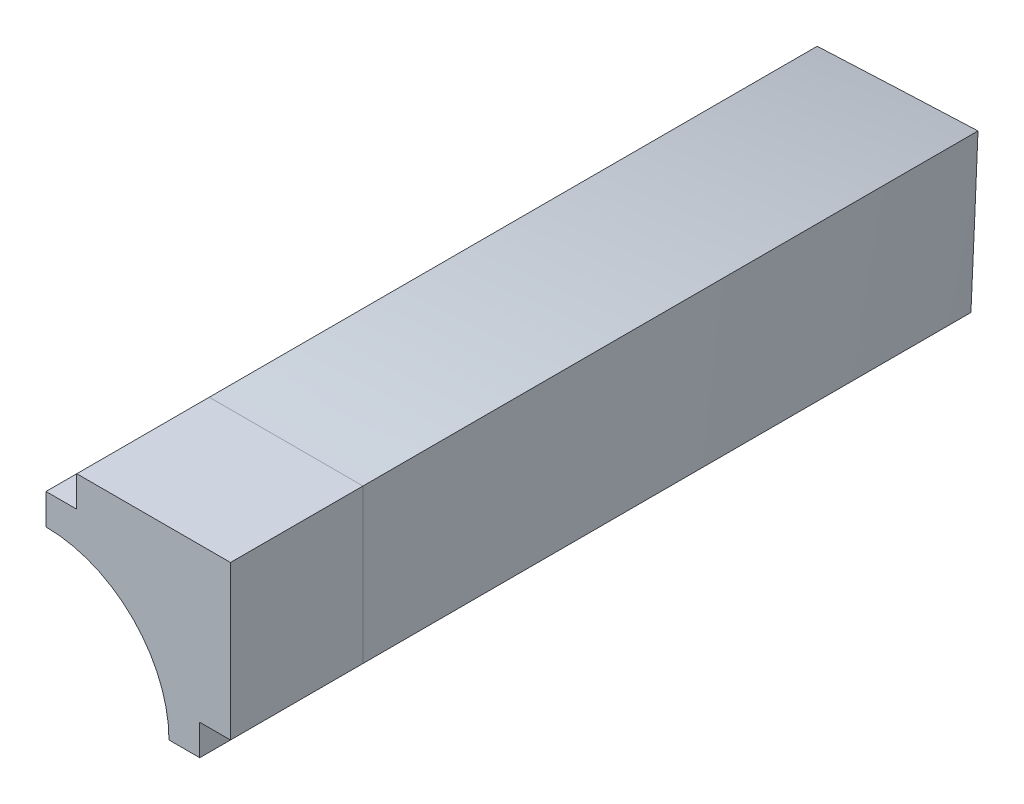
SolidWorks part; units mm, degrees
material "PET"
ref_plane "Front Plane" through (0, 0, 0) normal (0, 0, 1) x (1, 0, 0)
ref_plane "Top Plane" through (0, 0, 0) normal (0, 1, 0) x (1, 0, 0)
ref_plane "Right Plane" through (0, 0, 0) normal (1, 0, 0) x (0, 0, -1)
sketch "Sketch1" plane through (0, 0, 0) normal (0, 0, 1) x (1, 0, 0)
  line L0 (325, 305) -> (330, 305)
  line L1 (330, 305) -> (330, 310)
  line L2 (330, 310) -> (335, 310)
  line L3 (335, -335) -> (335, 335) construction
  line L4 (335, 310) -> (335, 335)
  line L5 (335, 335) -> (310, 335)
  line L6 (335, 335) -> (-335, 335) construction
  line L7 (310, 335) -> (310, 330)
  line L8 (310, 330) -> (305, 330)
  line L9 (305, 330) -> (305, 325)
  arc A0 (325, 305) -> (305, 325) centre (305, 305) ccw construction
  arc A1 (325, 305) -> (305, 325) centre (305, 305) ccw
  dimension "D1" = 5
  dimension "D2" = 5
extrude "Boss-Extrude1" add sketch "Sketch1" against normal up to vertex (21.5428 mm away)
sketch "Sketch3" plane through (0, 0, -21.5428) normal (0, 0, -1) x (-1, 0, 0)
  line L8 (-305, 325) -> (-305, 330)
  line L9 (-305, 330) -> (-310, 330)
  line L10 (-310, 330) -> (-310, 335)
  line L11 (-310, 335) -> (-335, 335)
  line L12 (-335, 335) -> (-335, 310)
  line L13 (-335, 310) -> (-330, 310)
  line L14 (-330, 310) -> (-330, 305)
  line L15 (-330, 305) -> (-325, 305)
  line L16 (-305, 325) -> (-305, 330)
  line L17 (-305, 330) -> (-310, 330)
  line L18 (-310, 330) -> (-310, 335)
  line L19 (-310, 335) -> (-335, 335)
  line L20 (-335, 335) -> (-335, 310)
  line L21 (-335, 310) -> (-330, 310)
  line L22 (-330, 310) -> (-330, 305)
  line L23 (-330, 305) -> (-325, 305)
  arc A1 (-305, 325) -> (-325, 305) centre (-305, 305) ccw
  arc A2 (-305, 325) -> (-325, 305) centre (-305, 305) ccw
  dimension "D1" = 0
ref_plane "Plane1" through (0, 0, 0) normal (0.7071, -0.7071, 0) x (-0.7071, -0.7071, 0)
sketch "Sketch4" plane through (0, 0, 0) normal (0.7071, -0.7071, 0) x (-0.7071, -0.7071, 0)
  spline S0 degree 3 poles (2194.5755, -1272.6797) (243.2691, -751.022) (-491.5801, -320.5935) (-449.365, 54.072) (-449.0492, 56.562) (-448.348, 61.5366) (-447.9624, 64.0213) (-446.7065, 71.4377) (-445.7359, 76.3418) (-442.4359, 90.9375) (-439.7192, 100.5126) (-262.3264, 621.3553) (1365.6763, 695.5304) (2438.329, 936.7288) knots -9.082141 -9.082141 -9.082141 -9.082141 0.25 0.25 0.3125 0.3125 0.375 0.375 0.5 0.5 0.75 0.75 14.313206 14.313206 14.313206 14.313206 only from (-451.3351, 21.5428) to (-425.4077, 137.7768) construction
  spline S1 degree 3 poles (-451.3351, 21.5428) (-451.3351, 31.5973) (-450.7692, 41.6093) (-449.365, 54.072) (-449.0492, 56.562) (-448.348, 61.5366) (-447.9624, 64.0213) (-446.7065, 71.4377) (-445.7359, 76.3418) (-442.4359, 90.9375) (-439.7192, 100.5126) (-433.298, 119.3656) (-429.5935, 128.6436) (-425.4077, 137.7768) knots 0 0 0 0 0.25 0.25 0.3125 0.3125 0.375 0.375 0.5 0.5 0.75 0.75 1 1 1 1
sweep "Sweep1" add profiles "Sketch3" path "Sketch4"
sketch "Sketch5" plane through (15.317, 15.317, 47.264) normal (-0.2946, -0.2946, -0.9091) x (-0.9556, 0.0908, 0.2803)
  line L8 (-284.3458, 333.8106) -> (-284.1079, 338.8049)
  line L9 (-284.1079, 338.8049) -> (-289.1023, 339.0428)
  line L10 (-289.1023, 339.0428) -> (-288.8644, 344.0372)
  line L11 (-288.8644, 344.0372) -> (-313.8361, 345.2265)
  line L12 (-313.8361, 345.2265) -> (-315.0255, 320.2548)
  line L13 (-315.0255, 320.2548) -> (-310.0311, 320.017)
  line L14 (-310.0311, 320.017) -> (-310.269, 315.0226)
  line L15 (-310.269, 315.0226) -> (-305.2747, 314.7848)
  line L16 (-284.3458, 333.8106) -> (-284.1079, 338.8049)
  line L17 (-284.1079, 338.8049) -> (-289.1023, 339.0428)
  line L18 (-289.1023, 339.0428) -> (-288.8644, 344.0372)
  line L19 (-288.8644, 344.0372) -> (-313.8361, 345.2265)
  line L20 (-313.8361, 345.2265) -> (-315.0255, 320.2548)
  line L21 (-315.0255, 320.2548) -> (-310.0311, 320.017)
  line L22 (-310.0311, 320.017) -> (-310.269, 315.0226)
  line L23 (-310.269, 315.0226) -> (-305.2747, 314.7848)
  arc A1 (-284.3458, 333.8106) -> (-305.2747, 314.7848) centre (-285.2973, 313.8333) ccw
  arc A2 (-284.3458, 333.8106) -> (-305.2747, 314.7848) centre (-285.2973, 313.8333) ccw
  dimension "D1" = 0
extrude "Boss-Extrude2" add sketch "Sketch5" along normal blind 10
sketch "Sketch6" plane through (0, 0, 0) normal (0, 1, 0) x (1, 0, 0)
  line L0 (256.4127, 138.6928) -> (356.7964, 138.6928)
  line L1 (-316.4912, 138.6928) -> (316.4912, 138.6928) construction
  line L2 (356.7964, 138.6928) -> (308.4821, 192.0611)
  line L3 (308.4821, 192.0611) -> (256.4127, 138.6928)
extrude "Cut-Extrude1" cut sketch "Sketch6" against normal through all both and the other way through all
